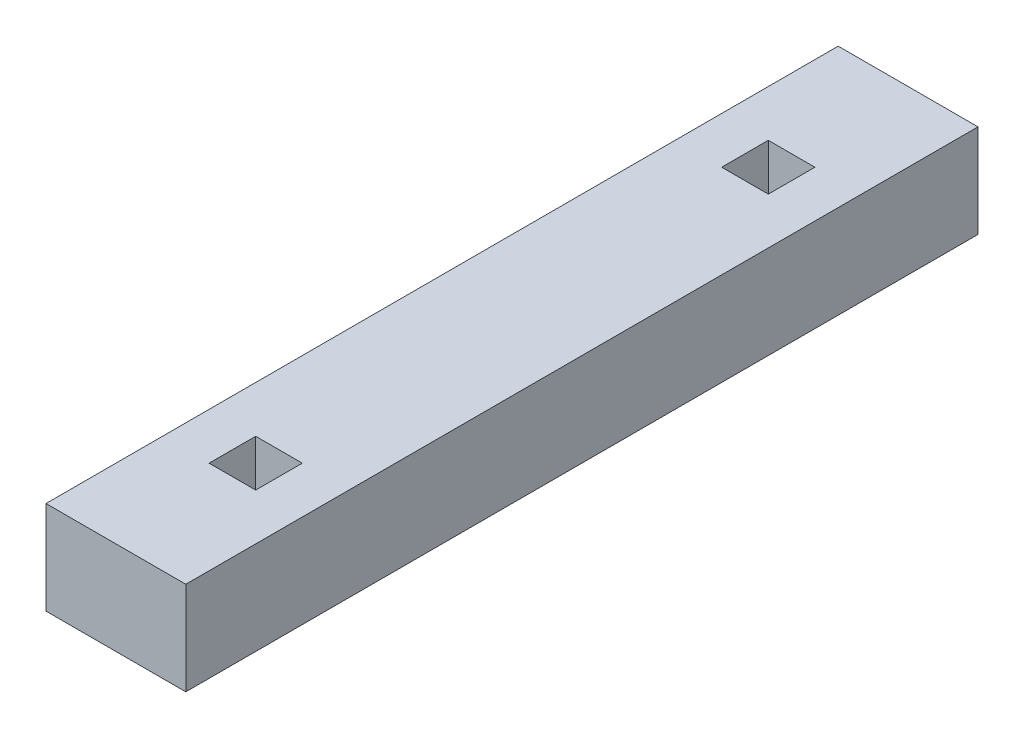
SolidWorks part; units mm, degrees
ref_plane "Front Plane" through (0, 0, 0) normal (0, 0, 1) x (1, 0, 0)
ref_plane "Top Plane" through (0, 0, 0) normal (0, 1, 0) x (1, 0, 0)
ref_plane "Right Plane" through (0, 0, 0) normal (1, 0, 0) x (0, 0, -1)
sketch "Sketch1" plane through (0, 0, 0) normal (0, 1, 0) x (1, 0, 0)
  line L0 (0, 80) -> (0, -90) construction
  line L1 (-15, 80) -> (15, 80)
  line L2 (-15, 80) -> (-15, -90)
  line L3 (-15, -90) -> (15, -90)
  line L4 (15, 80) -> (15, -90)
  line L5 (-5, 55) -> (5, 55)
  line L6 (-5, 55) -> (-5, 45)
  line L7 (-5, 45) -> (5, 45)
  line L8 (5, 55) -> (5, 45)
  line L9 (15, -5) -> (-15, -5) construction
  line L10 (-5, -65) -> (-5, -55)
  line L11 (-5, -55) -> (5, -55)
  line L12 (5, -65) -> (5, -55)
  line L13 (-5, -65) -> (5, -65)
  point P9 (0, 55)
  point P10 (0, 80)
  dimension "D3" = 10
  dimension "D5" = 100
  dimension "D4" = 10
  dimension "D1" = 30
  dimension "D2" = 170
extrude "Boss-Extrude1" add sketch "Sketch1" along normal blind 20
